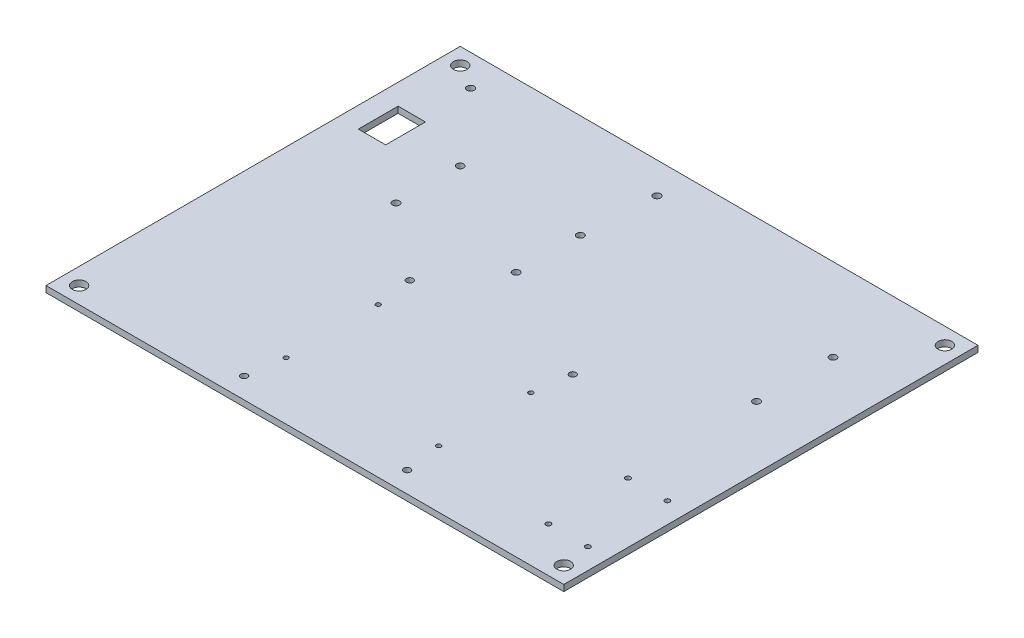
SolidWorks part; units mm, degrees
ref_plane "Front Plane" through (0, 0, 0) normal (0, 0, 1) x (1, 0, 0)
ref_plane "Top Plane" through (0, 0, 0) normal (0, 1, 0) x (1, 0, 0)
ref_plane "Right Plane" through (0, 0, 0) normal (1, 0, 0) x (0, 0, -1)
sketch "Sketch2" plane through (0, 0, 0) normal (0, 1, 0) x (1, 0, 0)
  line L1 (-125, -100) -> (125, -100)
  line L2 (-125, -100) -> (-125, 100)
  line L3 (-125, 100) -> (125, 100)
  line L4 (125, -100) -> (125, 100)
  line L5 (-125, -100) -> (125, 100) construction
  line L6 (-125, 100) -> (125, -100) construction
  point P0 (0, 0)
  dimension "D1" = 250
  dimension "D2" = 200
extrude "Boss-Extrude2" add sketch "Sketch2" along normal blind 3
sketch "Sketch3" plane through (0, 3, 0) normal (0, 1, 0) x (1, 0, 0)
  line L0 (-105, 85) -> (-15, 85) construction
  line L1 (125, 100) -> (-125, 100) construction
  line L2 (-125, 100) -> (-125, -100) construction
  line L3 (0, 100) -> (0, -100) construction
  line L4 (-115, 60) -> (-101.8, 60)
  line L5 (-115, 60) -> (-115, 40.8)
  line L6 (-115, 40.8) -> (-101.8, 40.8)
  line L7 (-101.8, 60) -> (-101.8, 40.8)
  line L8 (-125, -100) -> (125, -100) construction
  line L9 (125, 0) -> (-125, 0) construction
  line L10 (125, -100) -> (125, 100) construction
  line L11 (95, 60) -> (95, 23.07) construction
  line L12 (-75, 50) -> (-17, 50) construction
  line L13 (-75, 50) -> (-75, 19) construction
  line L14 (-75, 19) -> (-17, 19) construction
  line L15 (-17, 50) -> (-17, 19) construction
  line L17 (96, -40) -> (115, -40) construction
  line L18 (96, -40) -> (96, -78.4) construction
  line L19 (96, -78.4) -> (115, -78.4) construction
  line L20 (115, -40) -> (115, -78.4) construction
  line L21 (-36.85, -72.25) -> (36.85, -72.25) construction
  line L22 (-36.85, -72.25) -> (-36.85, -27.75) construction
  line L23 (-36.85, -27.75) -> (36.85, -27.75) construction
  line L24 (36.85, -72.25) -> (36.85, -27.75) construction
  line L25 (-36.85, -72.25) -> (36.85, -27.75) construction
  line L26 (-36.85, -27.75) -> (36.85, -72.25) construction
  line L27 (-39.35, -90) -> (39.35, -90) construction
  line L28 (-39.35, -90) -> (-39.35, -10) construction
  line L29 (-39.35, -10) -> (39.35, -10) construction
  line L30 (39.35, -90) -> (39.35, -10) construction
  line L31 (-39.35, -90) -> (39.35, -10) construction
  line L32 (-39.35, -10) -> (39.35, -90) construction
  circle A0 centre (-105, 85) radius 1.75
  circle A1 centre (-15, 85) radius 1.75
  circle A2 centre (-117, 92) radius 3.3
  circle A3 centre (-117, -92) radius 3.3
  circle A4 centre (117, 92) radius 3.3
  circle A5 centre (117, -92) radius 3.3
  circle A6 centre (-75, 50) radius 1.7
  circle A7 centre (-17, 50) radius 1.7
  circle A8 centre (-75, 19) radius 1.7
  circle A9 centre (-17, 19) radius 1.7
  circle A10 centre (95, 60) radius 1.7
  circle A11 centre (95, 23.07) radius 1.7
  circle A12 centre (96, -40) radius 1.2
  circle A13 centre (115, -40) radius 1.2
  circle A14 centre (115, -78.4) radius 1.2
  circle A15 centre (96, -78.4) radius 1.2
  circle A16 centre (-39.35, -10) radius 1.6
  circle A17 centre (39.35, -10) radius 1.6
  circle A18 centre (-39.35, -90) radius 1.6
  circle A19 centre (39.35, -90) radius 1.6
  circle A20 centre (-36.85, -27.75) radius 1.1
  circle A21 centre (36.85, -27.75) radius 1.1
  circle A22 centre (36.85, -72.25) radius 1.1
  circle A23 centre (-36.85, -72.25) radius 1.1
  point P48 (0, -50)
  point P53 (0, -50)
  dimension "D2" = 3.5
  dimension "D3" = 3.5
  dimension "D10" = 6.6
  dimension "D17" = 3.4
  dimension "D19" = 3.4
  dimension "D24" = 2.4
  dimension "D31" = 3.2
  dimension "D33" = 2.2
  dimension "D1" = 90
  dimension "D4" = 15
  dimension "D5" = 20
  dimension "D6" = 19.2
  dimension "D7" = 13.2
  dimension "D8" = 10
  dimension "D9" = 40
  dimension "D11" = 8
  dimension "D12" = 8
  dimension "D13" = 58
  dimension "D14" = 31
  dimension "D15" = 50
  dimension "D16" = 50
  dimension "D18" = 36.93
  dimension "D20" = 40
  dimension "D21" = 30
  dimension "D22" = 19
  dimension "D23" = 38.4
  dimension "D25" = 10
  dimension "D26" = 60
  dimension "D27" = 73.7
  dimension "D28" = 44.5
  dimension "D29" = 78.7
  dimension "D30" = 80
  dimension "D32" = 50
extrude "Cut-Extrude1" cut sketch "Sketch3" against normal up to surface (3 mm away) up to face at (0, 0, 0)
